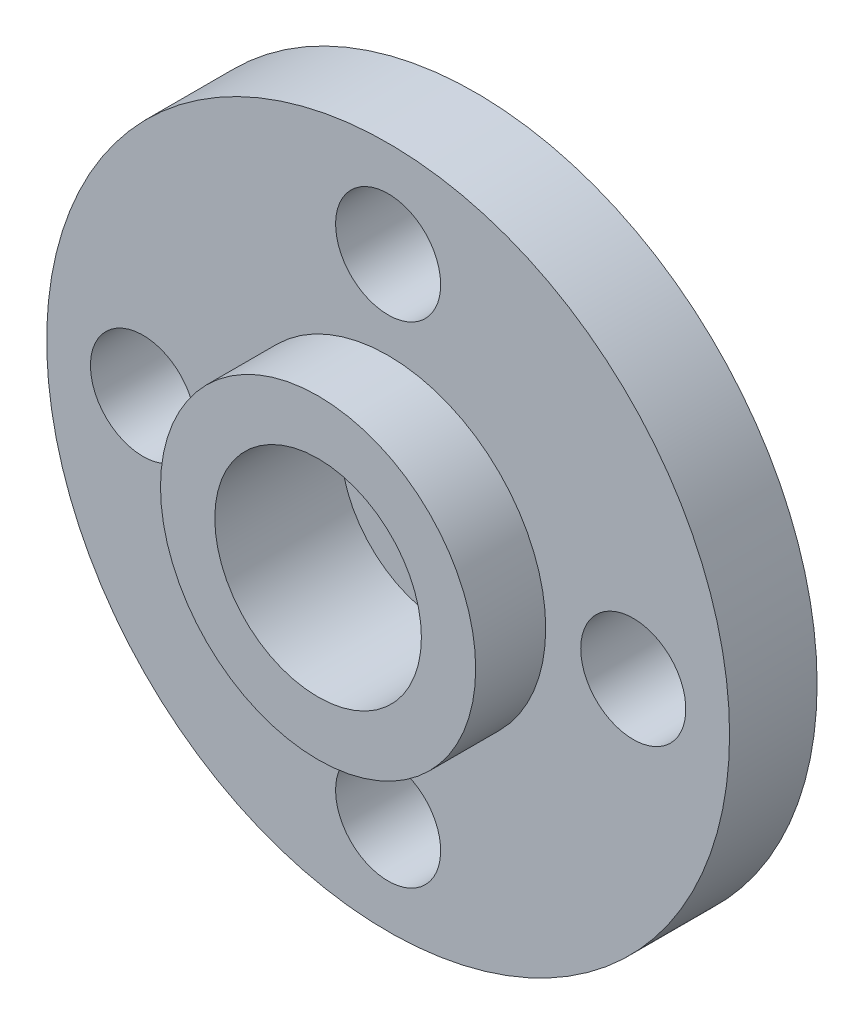
SolidWorks part; units mm, degrees
ref_plane "前视基准面" through (0, 0, 0) normal (0, 0, 1) x (1, 0, 0)
ref_plane "上视基准面" through (0, 0, 0) normal (0, 1, 0) x (1, 0, 0)
ref_plane "右视基准面" through (0, 0, 0) normal (1, 0, 0) x (0, 0, -1)
sketch "草图1" plane through (0, 0, 0) normal (0, 0, 1) x (1, 0, 0)
  circle A0 centre (0, 0) radius 9.75
extrude "凸台-拉伸1" add sketch "草图1" along normal blind 2.5
sketch "草图2" plane through (0, 0, 2.5) normal (0, 0, 1) x (1, 0, 0)
  circle A0 centre (0, 0) radius 4.5
extrude "凸台-拉伸2" add sketch "草图2" along normal blind 2
sketch "草图3" plane through (0, 0, 4.5) normal (0, 0, 1) x (1, 0, 0)
  circle A0 centre (0, 0) radius 2.95
extrude "切除-拉伸1" cut sketch "草图3" against normal blind 3.6
sketch "草图4" plane through (0, 0, 0) normal (0, 0, -1) x (-1, 0, 0)
  circle A0 centre (0, 0) radius 1.6
extrude "切除-拉伸2" cut sketch "草图4" against normal blind 3.6
sketch "草图5" plane through (0, 0, 2.5) normal (0, 0, 1) x (1, 0, 0)
  circle A0 centre (0, 0) radius 7 construction
  circle A1 centre (-7, 0) radius 1.5
  circle A2 centre (0, 0) radius 7 construction
  circle A3 centre (0, 0) radius 7 construction
  circle A4 centre (0, 0) radius 7 construction
  dimension "D1" = 4
extrude "切除-拉伸3" cut sketch "草图5" against normal through all
pattern_circular "阵列(圆周)1" count 4 over 360 about axis through (0, 0, 0) along (0, 0, 1) of "切除-拉伸3"
